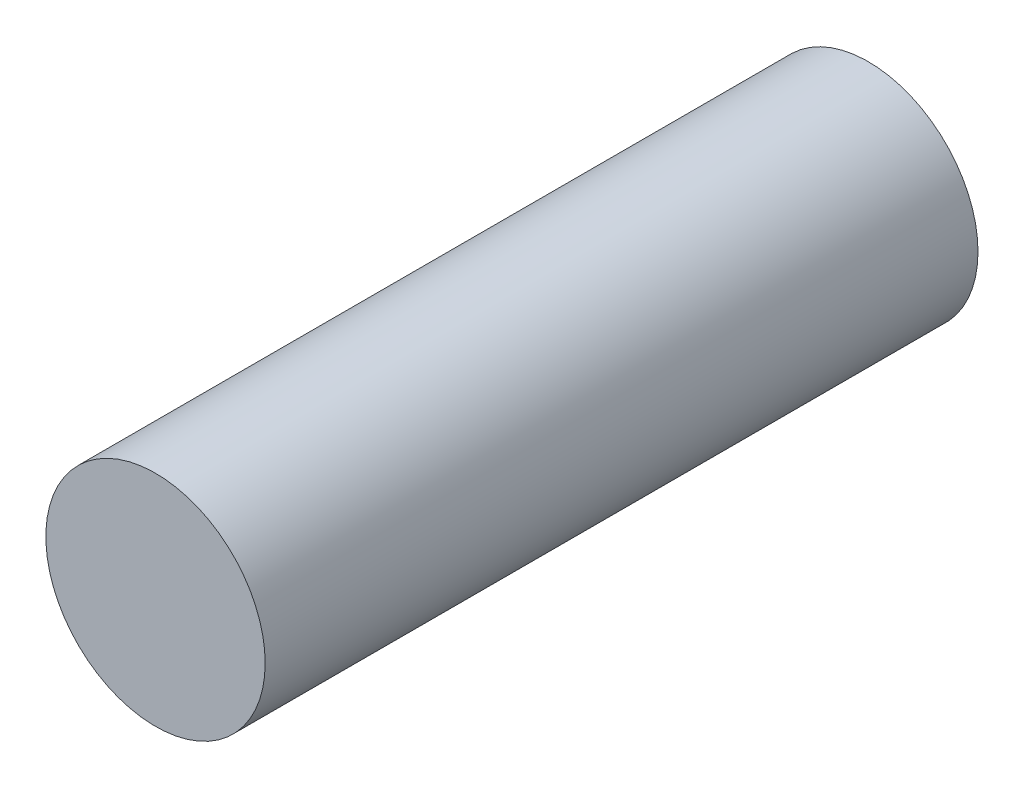
SolidWorks part; units mm, degrees
material "Copper"
ref_plane "Front Plane" through (0, 0, 0) normal (0, 0, 1) x (1, 0, 0)
ref_plane "Top Plane" through (0, 0, 0) normal (0, 1, 0) x (1, 0, 0)
ref_plane "Right Plane" through (0, 0, 0) normal (1, 0, 0) x (0, 0, -1)
ref_plane "Plane1" through (0, -43, 0) normal (0, 1, 0) x (1, 0, 0)
sketch "Sketch1" plane through (0, -43, 0) normal (0, 1, 0) x (1, 0, 0)
  line L0 (27, 4.5) -> (21, 4.5)
  line L1 (21, 4.5) -> (21, -34.5)
  line L2 (21, -34.5) -> (27, -34.5)
  line L3 (27, -34.5) -> (27, 4.5)
  line L4 (21, 4.5) -> (21, -34.5) construction
revolve "Revolve1" add sketch "Sketch1" angle 360 about L4
